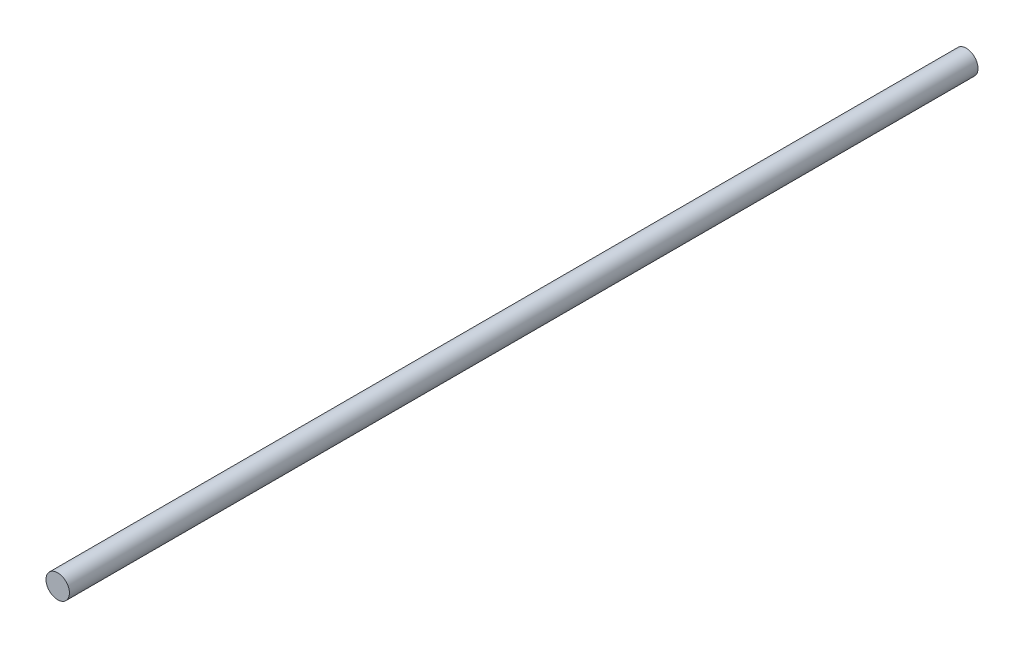
SolidWorks part; units mm, degrees
ref_plane "Plan de face" through (0, 0, 0) normal (0, 0, 1) x (1, 0, 0)
ref_plane "Plan de dessus" through (0, 0, 0) normal (0, 1, 0) x (1, 0, 0)
ref_plane "Plan de droite" through (0, 0, 0) normal (1, 0, 0) x (0, 0, -1)
sketch "Esquisse1" plane through (0, 0, 0) normal (0, 0, 1) x (1, 0, 0)
  circle A0 centre (0, 0) radius 4
  dimension "D1" = 8
extrude "Boss.-Extru.1" add sketch "Esquisse1" along normal blind 310
